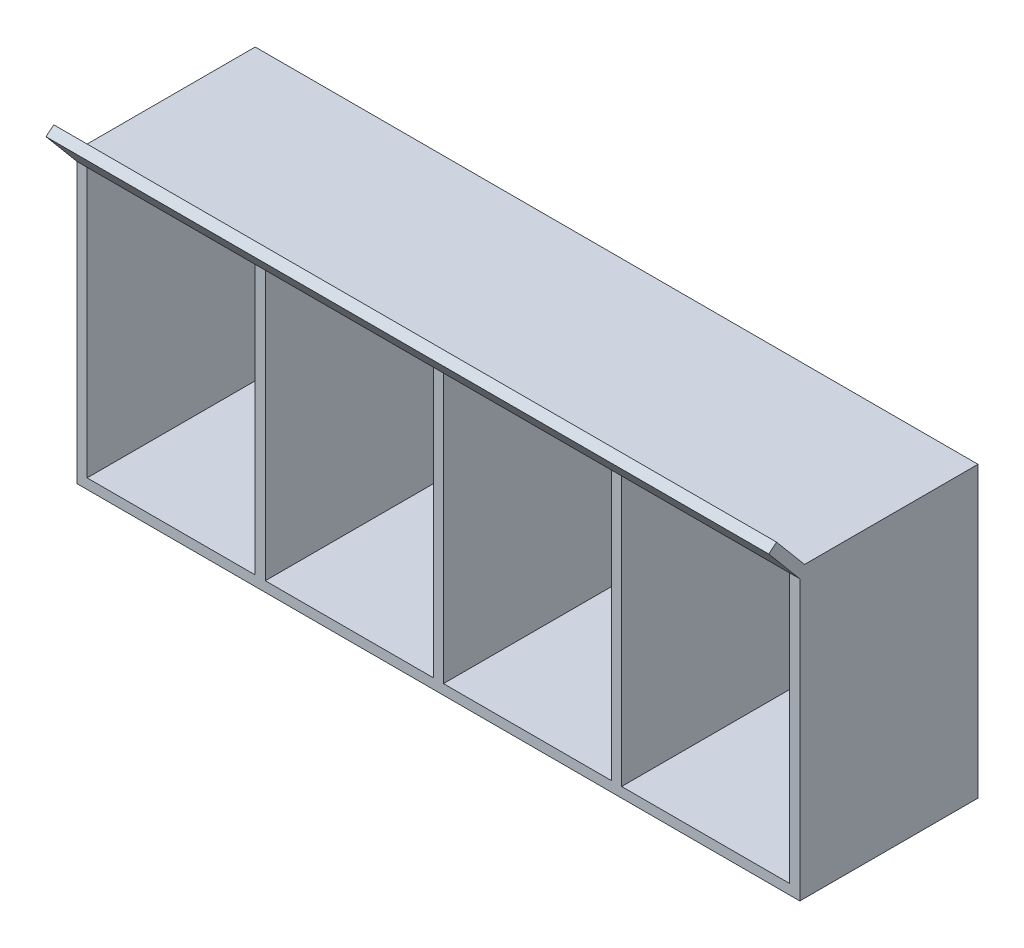
SolidWorks part; units mm, degrees
ref_plane "Plano frontal" through (0, 0, 0) normal (0, 0, 1) x (1, 0, 0)
ref_plane "Plano superior" through (0, 0, 0) normal (0, 1, 0) x (1, 0, 0)
ref_plane "Plano direito" through (0, 0, 0) normal (1, 0, 0) x (0, 0, -1)
sketch "Esboço1" plane through (0, 0, 0) normal (0, 0, 1) x (1, 0, 0)
  line L0 (0, 86) -> (215, 86)
  line L5 (0, 86) -> (0, 0)
  line L6 (0, 0) -> (215, 0)
  line L7 (3, 83) -> (53, 83)
  line L8 (0, 86) -> (53, 86)
  line L9 (0, 86) -> (0, 0)
  line L10 (0, 0) -> (53, 0)
  line L11 (56, 83) -> (56, 3)
  line L12 (53, 83) -> (53, 3)
  line L13 (56, 83) -> (56, 3)
  line L14 (3, 3) -> (53, 3)
  line L15 (3, 83) -> (3, 3)
  line L17 (53, 83) -> (53, 3)
  line L19 (56, 83) -> (106, 83)
  line L21 (106, 83) -> (106, 3)
  line L23 (53, 83) -> (53, 3)
  line L25 (109, 83) -> (109, 3)
  line L26 (106, 83) -> (106, 3)
  line L27 (109, 83) -> (109, 3)
  line L28 (56, 3) -> (106, 3)
  line L29 (56, 83) -> (56, 3)
  line L31 (109, 83) -> (159, 83)
  line L33 (106, 83) -> (106, 3)
  line L35 (162, 83) -> (162, 3)
  line L36 (159, 83) -> (159, 3)
  line L37 (162, 83) -> (162, 3)
  line L38 (109, 3) -> (159, 3)
  line L39 (109, 83) -> (109, 3)
  line L41 (159, 83) -> (159, 3)
  line L43 (162, 83) -> (212, 83)
  line L45 (159, 83) -> (159, 3)
  line L47 (215, 86) -> (215, 0)
  line L48 (212, 83) -> (212, 3)
  line L49 (215, 83) -> (215, 3)
  line L50 (162, 3) -> (212, 3)
  line L51 (162, 83) -> (162, 3)
  line L53 (212, 83) -> (212, 3)
  line L57 (212, 83) -> (212, 3)
  line L63 (215, 83) -> (215, 3)
  line L64 (56, 86) -> (56, 0) construction
  line L65 (0, 86) -> (56, 86) construction
  line L68 (0, 0) -> (56, 0) construction
  dimension "D1" = 3
  dimension "D2" = 50
  dimension "D3" = 80
  dimension "D4" = 80
  dimension "D5" = 80
  dimension "D6" = 80
extrude "Ressalto-extrusão1" add sketch "Esboço1" along normal blind 50
sketch "Esboço2" plane through (0, 0, 0) normal (0, 0, -1) x (-1, 0, 0)
  line L0 (0, 0) -> (-215, 0) construction
  line L1 (0, 86) -> (-215, 86)
  line L2 (0, 86) -> (0, 0)
  line L3 (0, 0) -> (-215, 0)
  line L4 (-215, 86) -> (-215, 0)
  line L5 (-215, 86) -> (-215, 0) construction
extrude "Ressalto-extrusão2" add sketch "Esboço2" along normal blind 3
sketch "Esboço3" plane through (0, 0, -3) normal (0, 0, -1) x (-1, 0, 0)
  line L0 (-215, 43) -> (0, 43) construction
  line L1 (-215, 86) -> (-215, 0) construction
  line L2 (0, 0) -> (0, 86) construction
  line L3 (-195, 86) -> (-195, 0) construction
  line L4 (0, 86) -> (-215, 86) construction
  line L5 (-107.5, 86) -> (-107.5, 0) construction
  line L6 (-215, 0) -> (0, 0) construction
  line L7 (-20, 86) -> (-20, 0) construction
  dimension "D1" = 20
  dimension "D2" = 20
sketch "Esboço4" plane through (215, 0, 0) normal (1, 0, 0) x (0, 0, -1)
  line L3 (-59.2301, 94) -> (-56.932, 95.9284)
  line L4 (-50, 86) -> (-50, 83)
  line L5 (-50, 86) -> (3, 86) construction
  line L10 (-56.932, 95.9284) -> (-48.6011, 86)
  line L11 (-50, 86) -> (-48.6011, 86)
  line L12 (-50, 83) -> (-59.2301, 94)
  dimension "D1" = 130
  dimension "D3" = 3
  dimension "D4" = 3
extrude "Ressalto-extrusão3" add sketch "Esboço4" against normal blind 215
